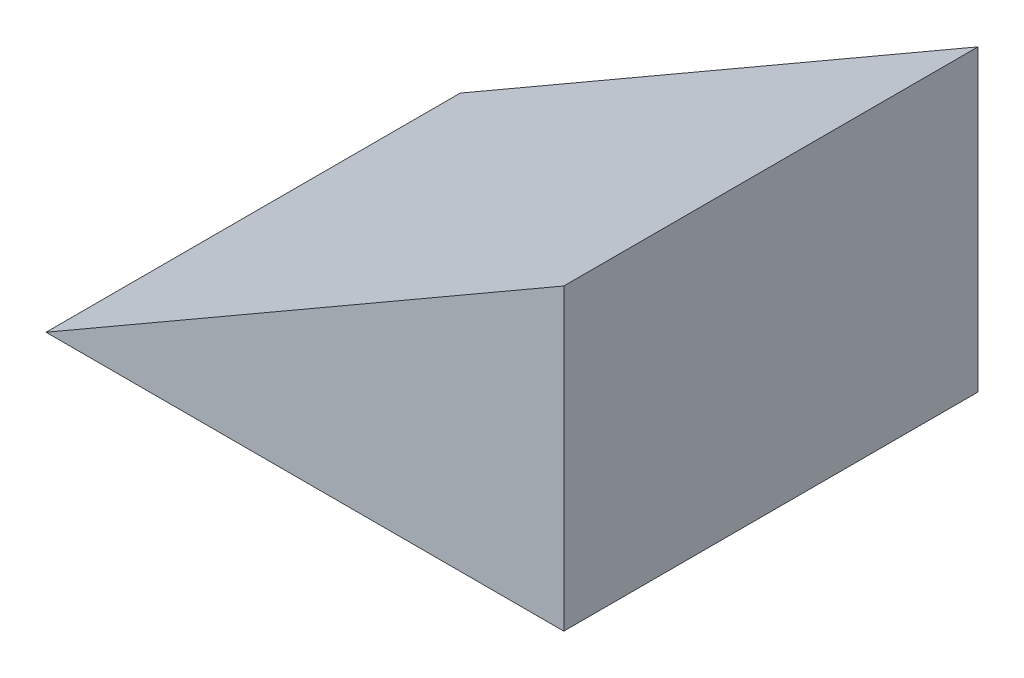
SolidWorks part; units mm, degrees
ref_plane "前基準面" through (0, 0, 0) normal (0, 0, 1) x (1, 0, 0)
ref_plane "上基準面" through (0, 0, 0) normal (0, 1, 0) x (1, 0, 0)
ref_plane "右基準面" through (0, 0, 0) normal (1, 0, 0) x (0, 0, -1)
sketch "草圖1" plane through (0, 0, 0) normal (0, 0, 1) x (1, 0, 0)
  line L0 (-15.2441, -20.1486) -> (-5.2441, -20.1486)
  line L1 (-5.2441, -20.1486) -> (-5.2441, -14.3751)
  line L2 (-5.2441, -14.3751) -> (-15.2441, -20.1486)
  dimension "D1" = 30
  dimension "D2" = 10
extrude "填料-伸長1" add sketch "草圖1" along normal blind 8
